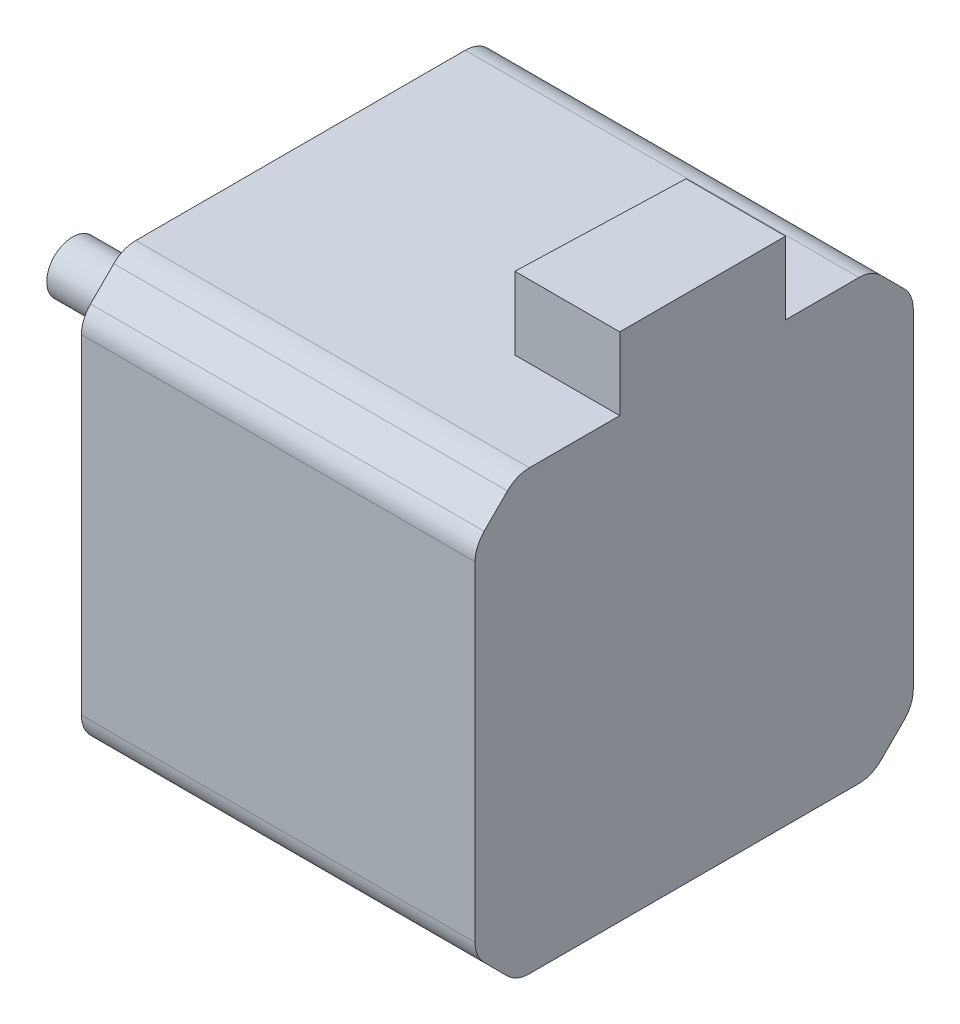
SolidWorks part; units mm, degrees
ref_plane "前视基准面" through (0, 0, 0) normal (0, 0, 1) x (1, 0, 0)
ref_plane "上视基准面" through (0, 0, 0) normal (0, 1, 0) x (1, 0, 0)
ref_plane "右视基准面" through (0, 0, 0) normal (1, 0, 0) x (0, 0, -1)
sketch "草图1" plane through (0, 0, 0) normal (1, 0, 0) x (0, 0, -1)
  line L0 (0.8787, 39.1787) -> (3.1213, 41.4213)
  line L1 (5.2426, 0) -> (37.0574, 0)
  line L2 (0, 5.2426) -> (0, 37.0574)
  line L3 (5.2426, 42.3) -> (37.0574, 42.3)
  line L4 (42.3, 5.2426) -> (42.3, 37.0574)
  line L5 (39.1787, 41.4213) -> (41.4213, 39.1787)
  line L6 (0.8787, 3.1213) -> (3.1213, 0.8787)
  line L7 (39.1787, 0.8787) -> (41.4213, 3.1213)
  arc A0 (39.1787, 41.4213) -> (37.0574, 42.3) centre (37.0574, 39.3) ccw
  arc A1 (41.4213, 39.1787) -> (42.3, 37.0574) centre (39.3, 37.0574) cw
  arc A2 (41.4213, 3.1213) -> (42.3, 5.2426) centre (39.3, 5.2426) ccw
  arc A3 (39.1787, 0.8787) -> (37.0574, 0) centre (37.0574, 3) cw
  arc A4 (3.1213, 0.8787) -> (5.2426, 0) centre (5.2426, 3) ccw
  arc A5 (0.8787, 3.1213) -> (0, 5.2426) centre (3, 5.2426) cw
  arc A6 (3.1213, 41.4213) -> (5.2426, 42.3) centre (5.2426, 39.3) cw
  arc A7 (0.8787, 39.1787) -> (0, 37.0574) centre (3, 37.0574) ccw
  point P0 (0, 0)
  point P1 (42.3, 42.3)
  point P2 (0, 42.3)
  point P3 (42.3, 0)
  point P15 (38.3, 42.3)
  point P18 (42.3, 38.3)
  point P21 (42.3, 4)
  point P24 (38.3, 0)
  point P27 (4, 0)
  point P30 (0, 4)
  point P33 (4, 42.3)
  point P36 (0, 38.3)
  dimension "D3" = 3
  dimension "D1" = 42.3
  dimension "D2" = 42.3
extrude "凸台-拉伸2" add sketch "草图1" along normal blind 38 contours L3 A0 L5 A1 L4 A2 L7 A3 L1 A4 L6 A5 L2 A7 L0 A6
sketch "草图2" plane through (0, 0, 0) normal (-1, 0, 0) x (0, 0, 1)
  circle A0 centre (-21.15, 21.15) radius 11
  dimension "D1" = 22
extrude "凸台-拉伸3" add sketch "草图2" along normal blind 2
fillet "圆角1" radius 1 1 edges at (-2, 21.15, -10.15)
sketch "草图3" plane through (-2, 0, 0) normal (-1, 0, 0) x (0, 0, 1)
  circle A0 centre (-21.15, 21.15) radius 2.5
extrude "凸台-拉伸4" add sketch "草图3" along normal blind 20 contours A0
sketch "草图4" plane through (0, 0, 0) normal (-1, 0, 0) x (0, 0, 1)
  circle A0 centre (-36.65, 36.65) radius 1.5
  dimension "D1" = 3
  dimension "D2" = 15.5
  dimension "D3" = 15.5
extrude "切除-拉伸1" cut sketch "草图4" against normal blind 4.5
pattern_circular "阵列(圆周)1" count 4 over 360 about axis through (0, 21.15, -21.15) along (1, 0, 0) of "切除-拉伸1"
sketch "草图6" plane through (0, 42.3, 0) normal (0, 1, 0) x (1, 0, 0)
  line L0 (28.4, 29.9675) -> (38, 29.9675)
  line L2 (28.4, 29.9675) -> (27.8726, 13.9675)
  line L3 (38, 5.2426) -> (38, 37.0574) construction
  line L4 (38, 29.9675) -> (38, 13.9675)
  line L5 (38, 13.9675) -> (27.8726, 13.9675)
  dimension "D1" = 16
  dimension "D2" = 9.6
extrude "凸台-拉伸5" add sketch "草图6" along normal blind 7
